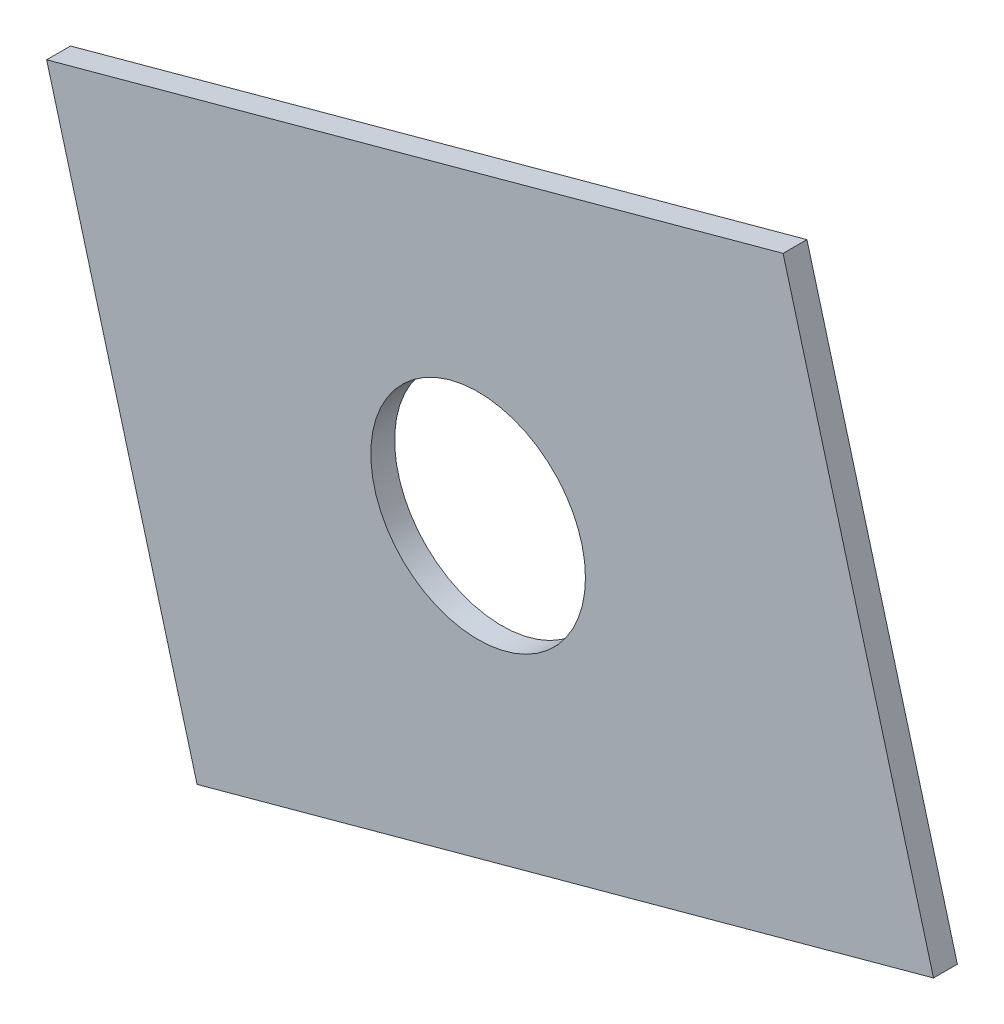
SolidWorks part; units mm, degrees
material "6061-T6 (SS)"
ref_plane "Front Plane" through (0, 0, 0) normal (0, 0, 1) x (1, 0, 0)
ref_plane "Top Plane" through (0, 0, 0) normal (0, 1, 0) x (1, 0, 0)
ref_plane "Right Plane" through (0, 0, 0) normal (1, 0, 0) x (0, 0, -1)
sketch "Sketch1" plane through (0, 0, 0) normal (0, 0, 1) x (1, 0, 0)
  line L8 (99.1957, 12.5856) -> (197.2253, 39.2829)
  line L9 (79.1727, 86.1078) -> (99.1957, 12.5856)
  line L10 (177.2023, 112.8052) -> (79.1727, 86.1078)
  line L11 (197.2253, 39.2829) -> (177.2023, 112.8052)
  circle A4 centre (136.607, 62.2618) radius 14.2875
extrude "Boss-Extrude1" add sketch "Sketch1" along normal blind 3.175
